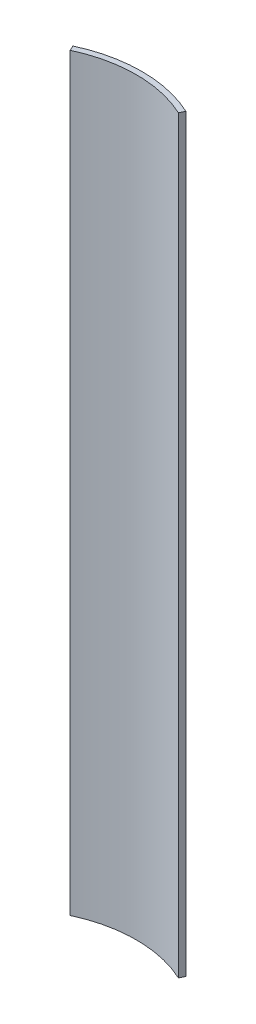
SolidWorks part; units mm, degrees
ref_plane "Front Plane" through (0, 0, 0) normal (0, 0, 1) x (1, 0, 0)
ref_plane "Top Plane" through (0, 0, 0) normal (0, 1, 0) x (1, 0, 0)
ref_plane "Right Plane" through (0, 0, 0) normal (1, 0, 0) x (0, 0, -1)
sketch "Sketch1" plane through (0, 0, 0) normal (0, 1, 0) x (1, 0, 0)
  line L0 (-30.8617, 66.1831) -> (-32.2035, 69.0607)
  line L1 (30.8617, 66.1831) -> (32.2035, 69.0607)
  line L2 (0, 0) -> (0, 76.2) construction
  arc A0 (32.2035, 69.0607) -> (-32.2035, 69.0607) centre (0, 0) ccw
  arc A1 (30.8617, 66.1831) -> (-30.8617, 66.1831) centre (0, 0) ccw
  dimension "D1" = 152.4
  dimension "D2" = 3.175
  dimension "D3" = 25
  dimension "D4" = 25
extrude "Boss-Extrude1" add sketch "Sketch1" along normal blind 427.1518
